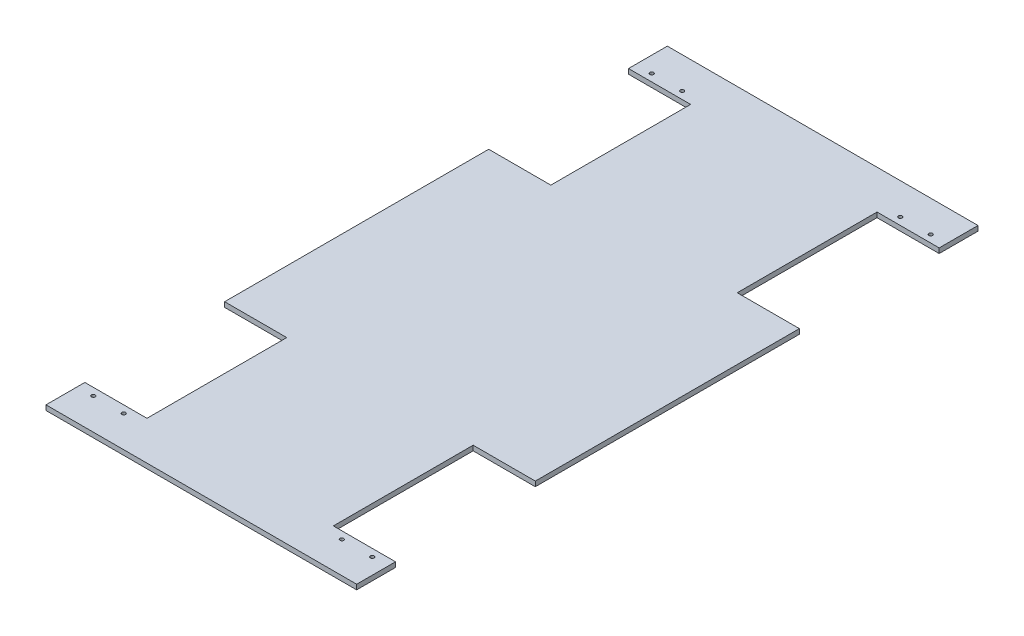
SolidWorks part; units mm, degrees
material "Balsa"
ref_plane "Front Plane" through (0, 0, 0) normal (0, 0, 1) x (1, 0, 0)
ref_plane "Top Plane" through (0, 0, 0) normal (0, 1, 0) x (1, 0, 0)
ref_plane "Right Plane" through (0, 0, 0) normal (1, 0, 0) x (0, 0, -1)
sketch "Sketch1" plane through (0, 0, 0) normal (0, 1, 0) x (1, 0, 0)
  line L0 (-100, 85) -> (-100, -85)
  line L1 (-100, 200) -> (100, 200)
  line L2 (-100, 200) -> (-100, 175)
  line L3 (-100, -200) -> (100, -200)
  line L4 (100, 200) -> (100, 175)
  line L5 (-100, 175) -> (-60, 175)
  line L7 (-100, 85) -> (-60, 85)
  line L8 (-60, 175) -> (-60, 85)
  line L9 (-100, -85) -> (-60, -85)
  line L11 (-100, -175) -> (-60, -175)
  line L12 (-60, -85) -> (-60, -175)
  line L13 (100, -175) -> (60, -175)
  line L15 (100, -85) -> (60, -85)
  line L17 (100, 175) -> (60, 175)
  line L19 (100, 85) -> (60, 85)
  line L20 (60, 175) -> (60, 85)
  line L21 (-100, -175) -> (-100, -200)
  line L22 (100, 85) -> (100, -85)
  line L23 (100, -175) -> (100, -200)
  line L24 (60, -85) -> (60, -175)
  point P4 (0, 200)
  point P6 (100, 0)
  dimension "D1" = 400
  dimension "D2" = 200
  dimension "D3" = 90
  dimension "D4" = 25
  dimension "D5" = 40
extrude "Boss-Extrude1" add sketch "Sketch1" along normal blind 3.175
hole_wizard "3/32 (0.09375) Diameter Hole1" positions "Sketch3" profile "Sketch4" hole size "3/32" standard "ANSI Inch" end condition up to next
sketch "Sketch3" plane through (0, 3.175, 0) normal (0, 1, 0) x (1, 0, 0)
  line L0 (-89.78, 179.7625) -> (-70.22, 179.7625) construction
  line L2 (-80, 175) -> (-80, 184.525) construction
  line L3 (-100, 175) -> (-60, 175) construction
  line L5 (-100, 200) -> (-100, 175) construction
  point P0 (-89.78, 179.7625)
  point P2 (-70.22, 179.7625)
  point P29 (-80, 179.7625)
  point P30 (-80, 179.7625)
  point P32 (0, 0)
  dimension "D1" = 19.56
  dimension "D2" = 4.7625
  dimension "D3" = 20
  dimension "D4" = 9.525
sketch "Sketch4" plane through (-89.78, 3.175, -179.7625) normal (1, 0, 0) x (0, 0, 1)
  line L0 (0, 0) -> (0, 3.175)
  line L1 (0, 3.175) -> (1.1906, 3.175)
  line L2 (1.1906, 3.175) -> (1.1906, 0)
  line L5 (1.1906, 0) -> (0, 0)
  line L11 (0, -6.35) -> (0, 107.95) construction
  dimension "Thru Hole Dia." = 2.3812
  dimension "Thru Hole Depth" = 3.175
mirror "Mirror5" about plane through (0, 0, 0) normal (1, 0, 0) of "3/32 (0.09375) Diameter Hole1" second plane through (0, 0, 0) second plane normal (0, 0, 1)
